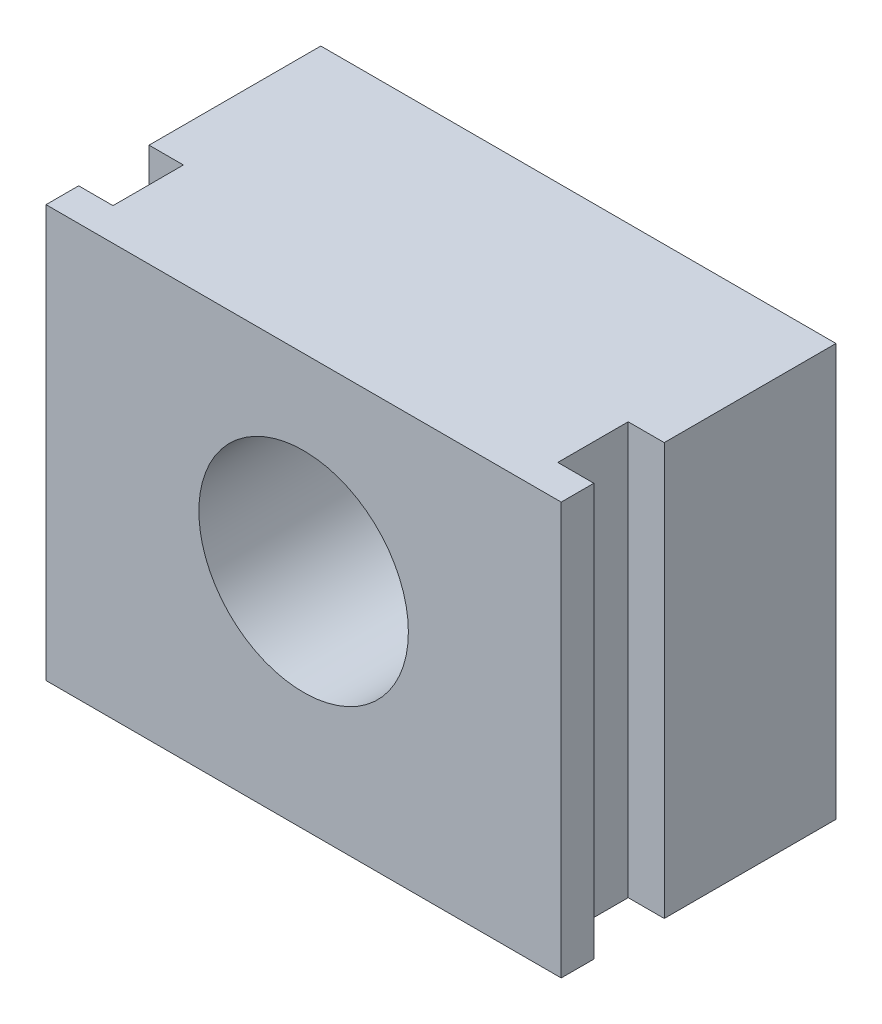
SolidWorks part; units mm, degrees
ref_plane "Plan de face" through (0, 0, 0) normal (0, 0, 1) x (1, 0, 0)
ref_plane "Plan de dessus" through (0, 0, 0) normal (0, 1, 0) x (1, 0, 0)
ref_plane "Plan de droite" through (0, 0, 0) normal (1, 0, 0) x (0, 0, -1)
sketch "Esquisse1" plane through (0, 0, 0) normal (0, 0, 1) x (1, 0, 0)
  line L1 (-7.5, 6) -> (7.5, 6)
  line L2 (-7.5, 6) -> (-7.5, -6)
  line L3 (-7.5, -6) -> (7.5, -6)
  line L4 (7.5, 6) -> (7.5, -6)
  dimension "D1" = 6
  dimension "D2" = 7.5
  dimension "D3" = 15
  dimension "D4" = 12
extrude "Boss.-Extru.1" add sketch "Esquisse1" along normal blind 5
sketch "Esquisse2" plane through (0, 0, 5) normal (0, 0, 1) x (1, 0, 0)
  line L0 (-6.5, 6) -> (-6.5, -6)
  line L1 (-6.5, 6) -> (6.45, 6)
  line L2 (-6.5, -6) -> (6.45, -6)
  line L3 (6.45, 6) -> (6.45, -6)
  line L4 (7.5, 6) -> (-7.5, 6) construction
  line L5 (-7.5, -6) -> (7.5, -6) construction
  line L6 (-7.5, 6) -> (-7.5, -6) construction
  dimension "D1" = 1
  dimension "D2" = 12.95
extrude "Boss.-Extru.2" add sketch "Esquisse2" along normal blind 2.05 contours L0 L1 L3 L2
sketch "Esquisse3" plane through (0, 0, 7.05) normal (0, 0, 1) x (1, 0, 0)
  line L1 (-7.5, 6) -> (7.5, 6)
  line L2 (-7.5, 6) -> (-7.5, -6)
  line L3 (-7.5, -6) -> (7.5, -6)
  line L4 (7.5, 6) -> (7.5, -6)
extrude "Boss.-Extru.3" add sketch "Esquisse3" along normal blind 0.95 contours L2 L1 L4 L3
sketch "Esquisse4" plane through (0, 0, 8) normal (0, 0, 1) x (1, 0, 0)
  line L0 (-7.5, 6) -> (7.5, 6) construction
  line L1 (-7.5, 6) -> (-7.5, -6) construction
  circle A0 centre (0, 0.5) radius 3.05
  dimension "D1" = 6.1
  dimension "D2" = 5.5
  dimension "D3" = 7.5
extrude "Enlèv. mat.-Extru.1" cut sketch "Esquisse4" against normal blind 8
